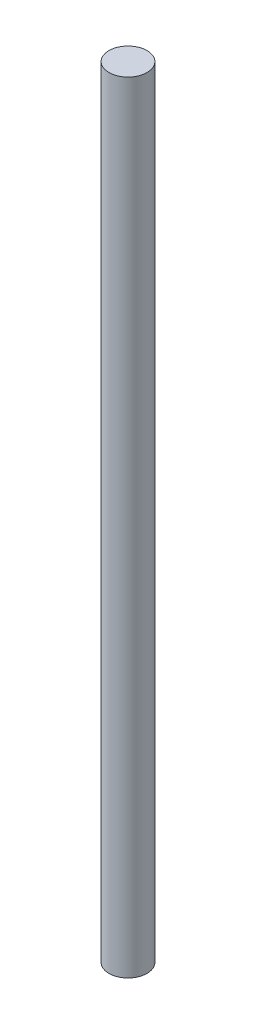
SolidWorks part; units mm, degrees
material "1060 合金"
ref_plane "前视基准面" through (0, 0, 0) normal (0, 0, 1) x (1, 0, 0)
ref_plane "上视基准面" through (0, 0, 0) normal (0, 1, 0) x (1, 0, 0)
ref_plane "右视基准面" through (0, 0, 0) normal (1, 0, 0) x (0, 0, -1)
other "Configuration Table"
sketch "草图1" plane through (0, 0, 0) normal (0, 1, 0) x (1, 0, 0)
  circle A0 centre (0, 0) radius 1
  dimension "D1" = 2
extrude "凸台-拉伸1" add sketch "草图1" along normal blind 41
